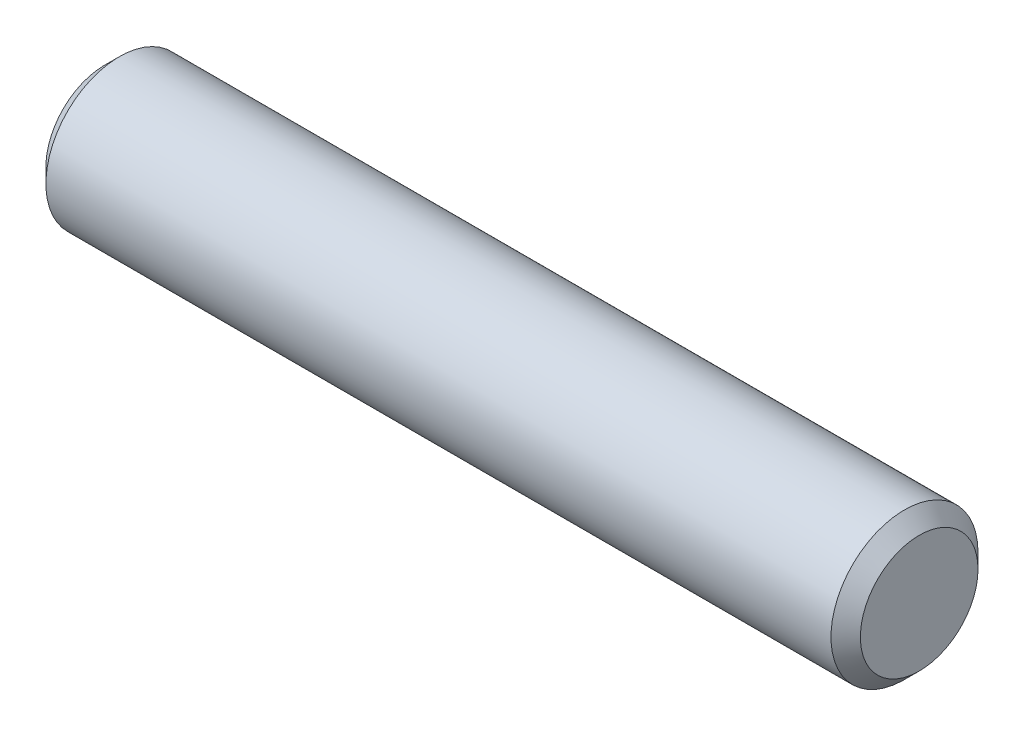
SolidWorks part; units mm, degrees
ref_plane "Front Plane" through (0, 0, 0) normal (0, 0, 1) x (1, 0, 0)
ref_plane "Top Plane" through (0, 0, 0) normal (0, 1, 0) x (1, 0, 0)
ref_plane "Right Plane" through (0, 0, 0) normal (1, 0, 0) x (0, 0, -1)
sketch "Sketch2" plane through (0, 0, 0) normal (1, 0, 0) x (0, 0, -1)
  circle A0 centre (0, 0) radius 5
  dimension "D1" = 10
extrude "Boss-Extrude1" add sketch "Sketch2" along normal blind 55.4
chamfer "Chamfer1" distance 1 angle 45 2 edges at (55.4, 0, -5) (0, 0, -5)
